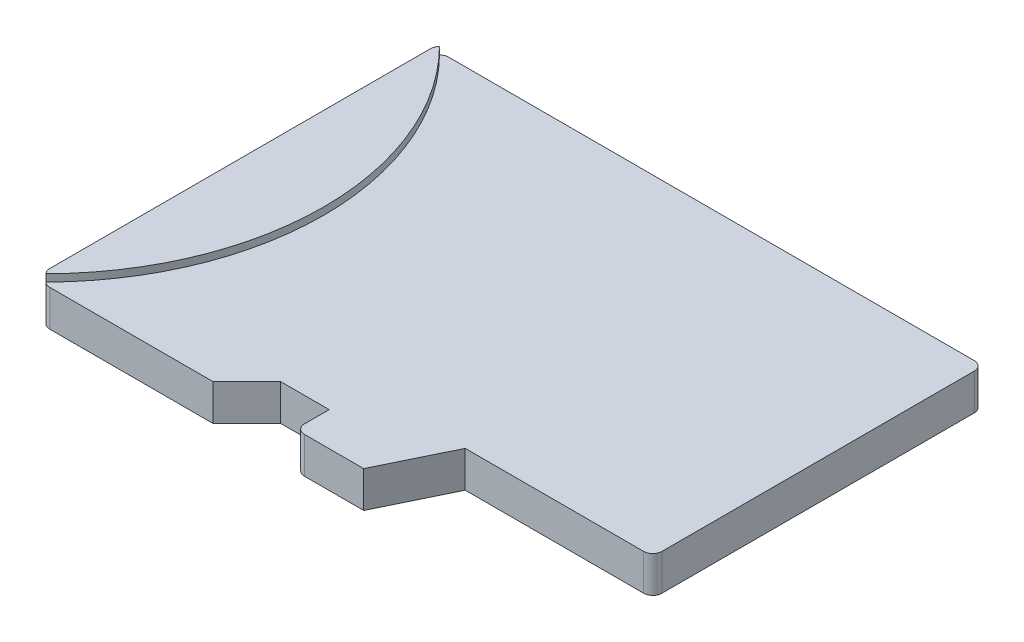
SolidWorks part; units mm, degrees
ref_plane "Front Plane" through (0, 0, 0) normal (0, 0, 1) x (1, 0, 0)
ref_plane "Top Plane" through (0, 0, 0) normal (0, 1, 0) x (1, 0, 0)
ref_plane "Right Plane" through (0, 0, 0) normal (1, 0, 0) x (0, 0, -1)
sketch "Sketch1" plane through (0, 0, 0) normal (0, 1, 0) x (1, 0, 0)
  line L0 (0, -55) -> (0, 55) construction
  line L1 (0, 11) -> (15, 11)
  line L2 (0, 11) -> (0, 0)
  line L3 (0, 0) -> (15, 0)
  line L4 (15, 11) -> (15, 0)
  line L5 (-55, 0) -> (55, 0) construction
  dimension "D1" = 15
  dimension "D2" = 11
extrude "Boss-Extrude1" add sketch "Sketch1" along normal blind 1
sketch "Sketch4" plane through (0, 1, 0) normal (0, 1, 0) x (1, 0, 0)
  line L5 (4.7494, 0) -> (5.6827, 0.9333)
  line L6 (-0.66, 0) -> (0.66, 0) construction
  line L7 (5.6827, 0.9333) -> (7.0246, 0.9333)
  line L8 (7.0246, 0.9333) -> (7.0246, 0)
  line L9 (7.0246, 0) -> (4.7494, 0)
extrude "Cut-Extrude3" cut sketch "Sketch4" against normal through all
sketch "Sketch6" plane through (0, 1, 0) normal (0, 1, 0) x (1, 0, 0)
  line L6 (8.9092, 0) -> (9.8261, 1.8835)
  line L7 (-0.66, 0) -> (0.66, 0) construction
  line L8 (9.8261, 1.8835) -> (15, 1.8835)
  line L9 (15, 0) -> (15, 11) construction
  line L10 (15, 1.8835) -> (15, 0)
  line L11 (15, 0) -> (8.9092, 0)
extrude "Cut-Extrude4" cut sketch "Sketch6" against normal through all
fillet "Fillet3" radius 0.25 1 edges at (15, 0.5, -1.8835)
fillet "Fillet4" radius 0.25 1 edges at (7.0246, 0.5, 0)
ref_plane "Plane4" through (0, 0, -5.5) normal (0, 0, -1) x (-1, 0, 0)
sketch "Sketch8" plane through (0, 1, 0) normal (0, 1, 0) x (1, 0, 0)
  line L0 (0.55, 5.5) -> (-0.55, 5.5) construction
  circle A0 centre (-5.3968, 5.5) radius 7.705
  dimension "D1" = 15.41
extrude "Boss-Extrude2" add sketch "Sketch8" along normal blind 0.2
sketch "Sketch12" plane through (0, 1.2, 0) normal (0, 1, 0) x (1, 0, 0)
  line L0 (0, 14.0041) -> (0, -3.0151)
  line L1 (0, -0.55) -> (0, 0.55) construction
  line L2 (0, -3.0151) -> (-14.5642, -3.0151)
  line L3 (-14.5642, -3.0151) -> (-14.5642, 14.0041)
  line L4 (-14.5642, 14.0041) -> (0, 14.0041)
extrude "Cut-Extrude5" cut sketch "Sketch12" against normal through all
fillet "Fillet5" radius 0.25 3 edges at (15, 0.5, -11) (0, 0.5, 0) (0, 0.5, -11)
